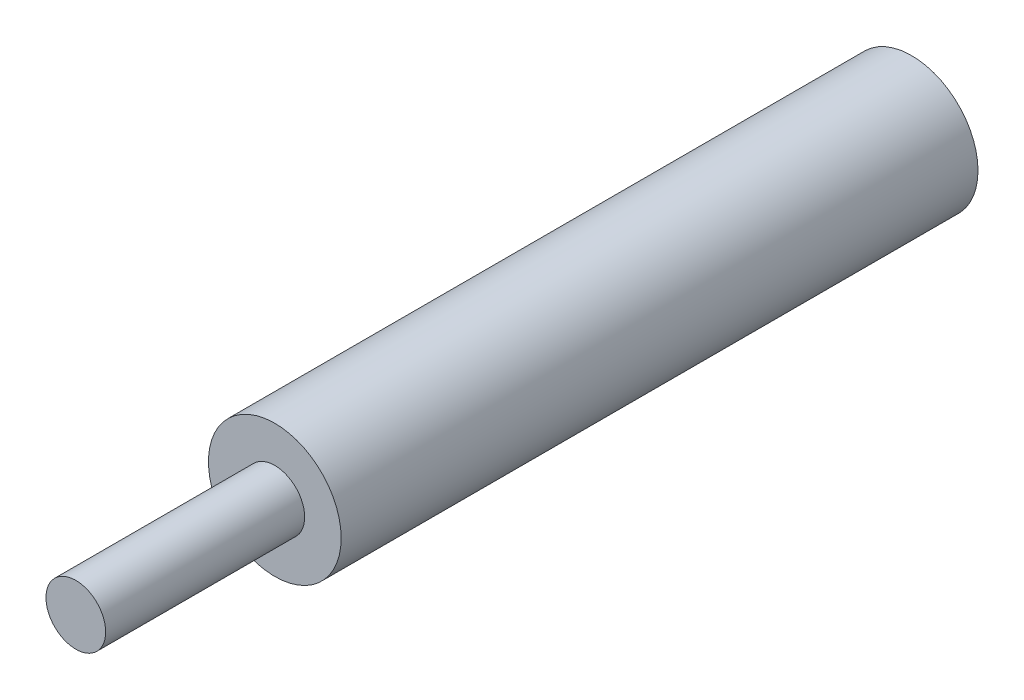
SolidWorks part; units mm, degrees
ref_plane "Front Plane" through (0, 0, 0) normal (0, 0, 1) x (1, 0, 0)
ref_plane "Top Plane" through (0, 0, 0) normal (0, 1, 0) x (1, 0, 0)
ref_plane "Right Plane" through (0, 0, 0) normal (1, 0, 0) x (0, 0, -1)
sketch "Sketch1" plane through (0, 0, 0) normal (0, 0, 1) x (1, 0, 0)
  circle A0 centre (0, 0) radius 16.675
  dimension "D1" = 33.35
extrude "Boss-Extrude1" add sketch "Sketch1" along normal mid plane 160
sketch "Sketch2" plane through (0, 0, 80) normal (0, 0, 1) x (1, 0, 0)
  circle A0 centre (0, 0) radius 7.5
  dimension "D1" = 15
extrude "Boss-Extrude2" add sketch "Sketch2" along normal blind 50
